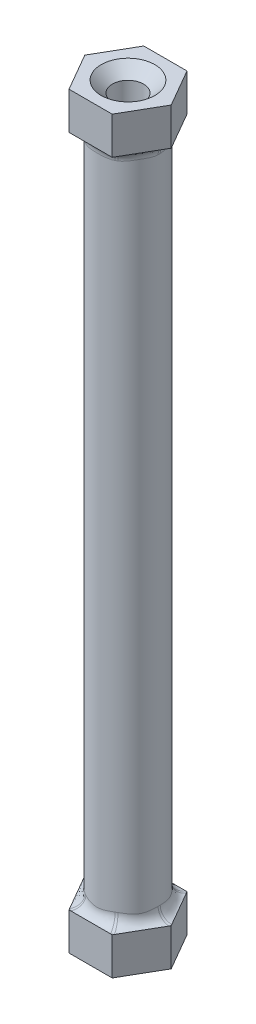
SolidWorks part; units mm, degrees
material "6061 合金"
ref_plane "前视基准面" through (0, 0, 0) normal (0, 0, 1) x (1, 0, 0)
ref_plane "上视基准面" through (0, 0, 0) normal (0, 1, 0) x (1, 0, 0)
ref_plane "右视基准面" through (0, 0, 0) normal (1, 0, 0) x (0, 0, -1)
sketch "草图1" plane through (0, 0, 0) normal (0, 1, 0) x (1, 0, 0)
  line L1 (1.7321, -3) -> (3.4641, 0)
  line L2 (3.4641, 0) -> (1.7321, 3)
  line L3 (1.7321, 3) -> (-1.7321, 3)
  line L4 (-1.7321, 3) -> (-3.4641, 0)
  line L5 (-3.4641, 0) -> (-1.7321, -3)
  line L6 (-1.7321, -3) -> (1.7321, -3)
  circle A0 centre (0, 0) radius 3 construction
  dimension "D1" = 6
extrude "凸台-拉伸1" add sketch "草图1" along normal blind 3
sketch "草图2" plane through (0, 3, 0) normal (0, 1, 0) x (1, 0, 0)
  circle A0 centre (0, 0) radius 2.5
  dimension "D1" = 5
extrude "凸台-拉伸2" add sketch "草图2" along normal blind 54
sketch "草图3" plane through (0, 57, 0) normal (0, 1, 0) x (1, 0, 0)
  line L6 (-1.7321, -3) -> (1.7321, -3)
  line L7 (1.7321, -3) -> (3.4641, 0)
  line L8 (3.4641, 0) -> (1.7321, 3)
  line L9 (1.7321, 3) -> (-1.7321, 3)
  line L10 (-1.7321, 3) -> (-3.4641, 0)
  line L11 (-3.4641, 0) -> (-1.7321, -3)
  line L12 (-1.7321, -3) -> (1.7321, -3)
  line L13 (1.7321, -3) -> (3.4641, 0)
  line L14 (3.4641, 0) -> (1.7321, 3)
  line L15 (1.7321, 3) -> (-1.7321, 3)
  line L16 (-1.7321, 3) -> (-3.4641, 0)
  line L17 (-3.4641, 0) -> (-1.7321, -3)
  dimension "D1" = 0
extrude "凸台-拉伸3" add sketch "草图3" along normal blind 3
fillet "圆角1" radius 0.9 2 edges at (0, 3, 2.5) (0, 57, 2.5)
hole_wizard "M3 螺纹孔1" positions "草图5" profile "草图6" tap size "M3" standard "GB"
sketch "草图5" plane through (0, 60, 0) normal (0, 1, 0) x (1, 0, 0)
  point P0 (0, 0)
sketch "草图6" plane through (0, 60, 0) normal (1, 0, 0) x (0, 0, 1)
  line L0 (0, 0) -> (0, 10.2511)
  line L1 (0, 10.2511) -> (1.25, 9.5)
  line L2 (1.25, 9.5) -> (1.25, 0)
  line L5 (1.25, 0) -> (0, 0)
  line L10 (0, 10.2511) -> (-1.25, 9.5) construction
  line L11 (0, -6.35) -> (0, 107.95) construction
  dimension "螺纹孔钻头直径" = 2.5
  dimension "螺纹孔钻头深度" = 9.5
  dimension "导头角度" = 118
cosmetic thread "孔螺蚊线1" parameters "D1"=8, "D2"=3
hole_wizard "M3 螺纹孔2" positions "草图7" profile "草图8" tap size "M3" standard "GB"
sketch "草图7" plane through (0, 0, 0) normal (0, -1, 0) x (-1, 0, 0)
  point P0 (0, 0)
sketch "草图8" plane through (0, 0, 0) normal (1, 0, 0) x (0, 0, -1)
  line L0 (0, 0) -> (0, 10.2511)
  line L1 (0, 10.2511) -> (1.25, 9.5)
  line L2 (1.25, 9.5) -> (1.25, 0)
  line L5 (1.25, 0) -> (0, 0)
  line L10 (0, 10.2511) -> (-1.25, 9.5) construction
  line L11 (0, -6.35) -> (0, 107.95) construction
  dimension "螺纹孔钻头直径" = 2.5
  dimension "螺纹孔钻头深度" = 9.5
  dimension "导头角度" = 118
cosmetic thread "孔螺蚊线2" parameters "D1"=8, "D2"=3
chamfer "倒角1" distance 0.9 angle 45 2 edges at (0, 0, -1.25) (0, 60, 1.25)
